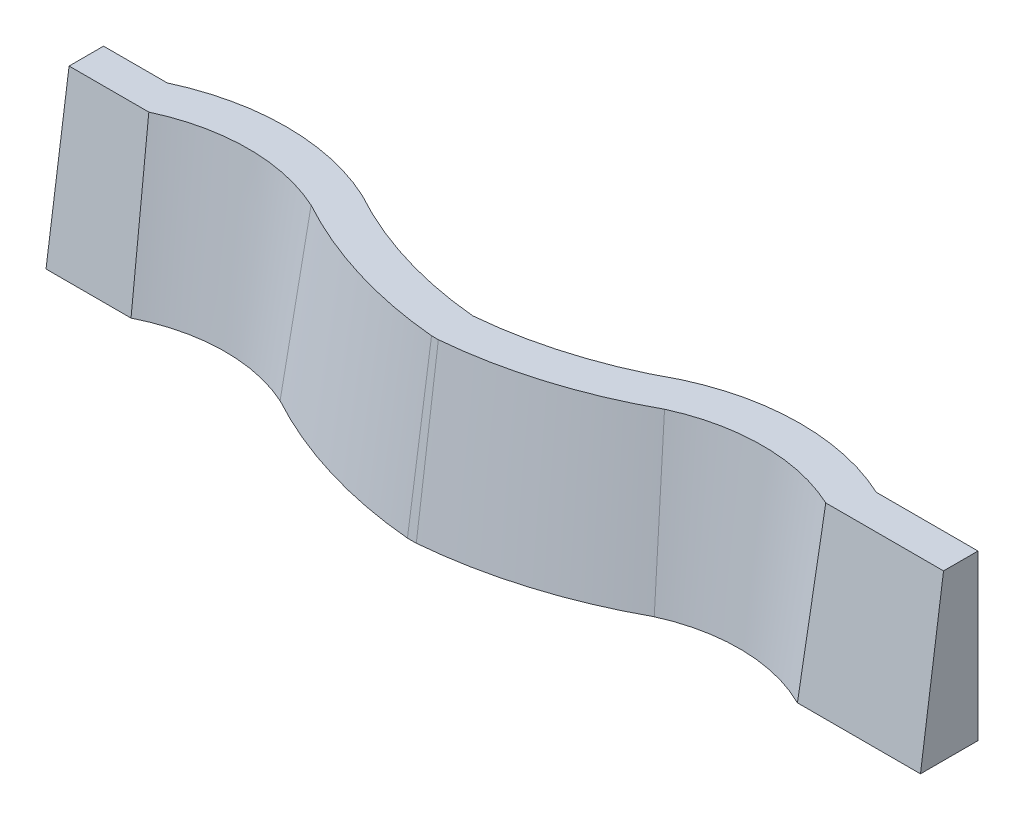
SolidWorks part; units mm, degrees
ref_plane "Front Plane" through (0, 0, 0) normal (0, 0, 1) x (1, 0, 0)
ref_plane "Top Plane" through (0, 0, 0) normal (0, 1, 0) x (1, 0, 0)
ref_plane "Right Plane" through (0, 0, 0) normal (1, 0, 0) x (0, 0, -1)
sketch "Sketch1" plane through (0, 0, 0) normal (0, 1, 0) x (1, 0, 0)
  line L0 (-110, -30) -> (-110, -41.2422) construction
  line L1 (-39.8399, -30) -> (34.8399, -30) construction
  line L2 (110, -30) -> (110, -41.2422) construction
  line L3 (0, -142.6423) -> (0, 36.4059) construction
  line L4 (0, -100) -> (0, 70) construction
  line L5 (-42.9151, -50) -> (42.9151, -50) construction
  line L6 (-110, -41.2422) -> (-39.8399, -43.9889) construction
  line L7 (39.8399, -43.9889) -> (110, -41.2422) construction
  line L8 (-110, -30) -> (-39.8399, -30) construction
  line L9 (110, -30) -> (34.8399, -30) construction
  line L10 (-39.8399, -30) -> (-39.8399, -43.9889) construction
  line L11 (34.8399, -30) -> (39.8399, -43.9889) construction
  arc A0 (-39.8399, -30) -> (34.8399, -30) centre (-2.5, 38.0274) ccw construction
  arc A1 (-39.8399, -43.9889) -> (0, -50) centre (-1.9011, 72.4289) ccw construction
  arc A2 (39.8399, -43.9889) -> (0, -50) centre (1.9011, 72.4289) cw construction
  dimension "D1" = 77.6015
  dimension "D2" = 122.4436
  dimension "D3" = 34.8399
  dimension "D4" = 70.1601
  dimension "D5" = 70.1601
  dimension "D6" = 92.242
  dimension "D7" = 13.9889
ref_plane "Bottom Of Chassis" through (0, -19.2, 0) normal (0, 1, 0) x (1, 0, 0)
ref_plane "Top of Chassis" through (0, 24, 0) normal (0, 1, 0) x (1, 0, 0)
sketch "Sketch3" plane through (0, 24, 0) normal (0, 1, 0) x (1, 0, 0)
  line L6 (-0.8962, -52.8359) -> (0.8962, -52.8359)
  line L7 (-110, -30) -> (-110, -39.0641)
  line L12 (-110, -39.0641) -> (-89.0261, -39.0641)
  line L13 (-110, -30) -> (-93.25, -30)
  line L16 (89.0261, -39.0641) -> (120, -39.0641) construction
  line L17 (89.0261, -39.0641) -> (120, -39.0641)
  line L18 (120, -30) -> (120, -39.0641) construction
  line L19 (120, -30) -> (120, -39.0641)
  line L20 (93.25, -30) -> (120, -30)
  arc A8 (-46.4813, -38.9279) -> (-89.0261, -39.0641) centre (-67.6063, -85.0296) ccw construction
  arc A9 (-93.25, -30) -> (-41.9625, -30) centre (-67.6063, -85.0296) cw
  arc A13 (-41.9625, -30) -> (-93.25, -30) centre (-67.6063, -85.0296) ccw construction
  arc A14 (-89.0261, -39.0641) -> (-46.4813, -38.9279) centre (-67.6063, -85.0296) cw
  arc A15 (-46.4813, -38.9279) -> (-0.8962, -52.8359) centre (9.5248, 62.9793) ccw
  arc A20 (-46.4813, -38.9279) -> (-0.8962, -52.8359) centre (9.5248, 62.9793) ccw construction
  arc A21 (-41.9625, -30) -> (0, -42.8761) centre (9.5248, 62.9793) ccw
  arc A22 (-41.9625, -30) -> (0, -42.8761) centre (9.5248, 62.9793) ccw construction
  arc A23 (0.8962, -52.8359) -> (46.4813, -38.9279) centre (-9.5248, 62.9793) ccw
  arc A24 (0.8962, -52.8359) -> (46.4813, -38.9279) centre (-9.5248, 62.9793) ccw construction
  arc A25 (0, -42.8761) -> (41.9625, -30) centre (-9.5248, 62.9793) ccw
  arc A26 (0, -42.8761) -> (41.9625, -30) centre (-9.5248, 62.9793) ccw construction
  arc A27 (93.25, -30) -> (41.9625, -30) centre (67.6063, -85.0296) ccw construction
  arc A28 (93.25, -30) -> (41.9625, -30) centre (67.6063, -85.0296) ccw
  arc A29 (89.0261, -39.0641) -> (46.4813, -38.9279) centre (67.6063, -85.0296) ccw construction
  arc A30 (89.0261, -39.0641) -> (46.4813, -38.9279) centre (67.6063, -85.0296) ccw
  point P19 (-27.3251, -36.417)
  point P20 (-73.6989, -83.1159)
  point P21 (0, -17.3273)
  point P27 (-70.2175, -80.192)
  point P44 (-112.1058, -33.2855)
extrude "Boss-Extrude1" add sketch "Sketch3" against normal up to surface (43.2 mm away) up to plane "Bottom Of Chassis"
draft "Draft2" type of draft neutral plane draft angle 8 faces to draft 7 face at (0, 2.4, 52.8359) face at (104.5131, 2.4, 39.0641) face at (67.7612, 2.4, 36.6573) face at (24.0488, 2.4, 47.0621) face at (-24.0488, 2.4, 47.0621) face at (-67.7612, 2.4, 36.6573) face at (-99.5131, 2.4, 39.0641) neutral plane through (0, 24, 0) neutral plane normal (0, 1, 0) parameters "D1"=8
